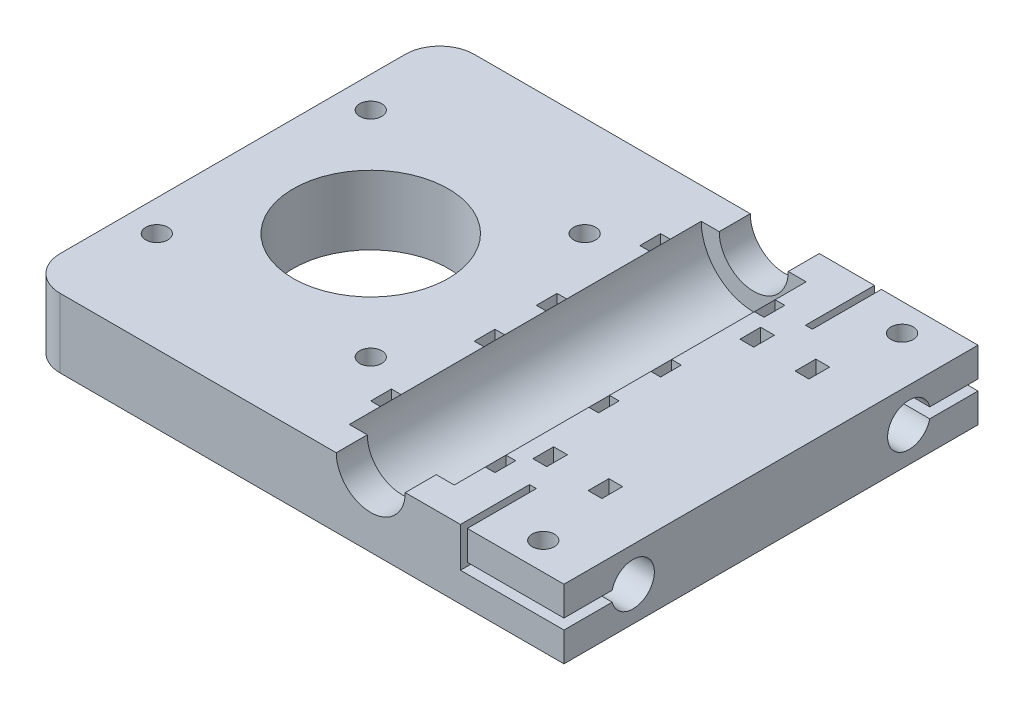
SolidWorks part; units mm, degrees
ref_plane "前基準面" through (0, 0, 0) normal (0, 0, 1) x (1, 0, 0)
ref_plane "上基準面" through (0, 0, 0) normal (0, 1, 0) x (1, 0, 0)
ref_plane "右基準面" through (0, 0, 0) normal (1, 0, 0) x (0, 0, -1)
sketch "草圖2" plane through (0, 0, 0) normal (0, 1, 0) x (1, 0, 0)
  line L1 (-20000, 30000) -> (20000, 30000)
  line L2 (-20000, 30000) -> (-20000, -30000)
  line L3 (-20000, -30000) -> (20000, -30000)
  line L4 (20000, 30000) -> (20000, -30000)
  line L5 (-20000, 30000) -> (20000, -30000) construction
  line L6 (-20000, -30000) -> (20000, 30000) construction
  point P0 (0, 0)
  dimension "D1" = 40000
  dimension "D2" = 60000
extrude "填料-伸長1" add sketch "草圖2" along normal blind 10000
sketch "草圖4" plane through (0, 0, 0) normal (0, 0, 1) x (1, 0, 0)
  line L0 (-20000, 10000) -> (20000, 10000) construction
  line L1 (-20000, 10000) -> (-20000, 0) construction
  circle A0 centre (-8000, 10000) radius 7600
  dimension "D1" = 15200
  dimension "D2" = 12000
extrude "除料-伸長2" cut sketch "草圖4" against normal mid plane 51000
sketch "草圖5" plane through (0, 0, 0) normal (0, 0, 1) x (1, 0, 0)
  circle A0 centre (-8000, 10000) radius 5000
  dimension "D1" = 10000
extrude "除料-伸長3" cut sketch "草圖5" against normal mid plane 80000
sketch "草圖6" plane through (0, 10000, 0) normal (0, 1, 0) x (1, 0, 0)
  line L0 (7000, 30000) -> (7000, -30000) construction
  line L1 (20000, 30000) -> (-3000, 30000) construction
  line L2 (-3000, -30000) -> (20000, -30000) construction
  line L3 (-13000, 25500) -> (-3000, 25500) construction
  line L4 (-20000, 0) -> (38738.6802, 0) construction
  line L5 (4000, 16500) -> (10000, 16500) construction
  line L6 (4000, 16500) -> (4000, 13500) construction
  line L7 (4000, 13500) -> (10000, 13500) construction
  line L8 (10000, 16500) -> (10000, 13500) construction
  line L9 (4000, 16500) -> (10000, 13500) construction
  line L10 (4000, 13500) -> (10000, 16500) construction
  line L11 (-20000, 30000) -> (-20000, -30000) construction
  line L12 (12000, -16500) -> (12000, -13500)
  line L13 (4000, 16500) -> (2000, 16500)
  line L14 (4000, 16500) -> (4000, 13500)
  line L15 (4000, 13500) -> (2000, 13500)
  line L16 (2000, 16500) -> (2000, 13500)
  line L17 (10000, 16500) -> (12000, 16500)
  line L18 (10000, 16500) -> (10000, 13500)
  line L19 (10000, 13500) -> (12000, 13500)
  line L20 (12000, 16500) -> (12000, 13500)
  line L21 (10000, -16500) -> (12000, -16500)
  line L22 (10000, -16500) -> (10000, -13500)
  line L23 (4000, -13500) -> (2000, -13500)
  line L24 (10000, -13500) -> (12000, -13500)
  line L25 (4000, -16500) -> (4000, -13500)
  line L26 (2000, -16500) -> (2000, -13500)
  line L27 (4000, -16500) -> (2000, -16500)
  point P8 (-8000, 25500)
  point P9 (7000, 15000)
  dimension "D1" = 15000
  dimension "D2" = 6000
  dimension "D3" = 3000
  dimension "D4" = 15000
  dimension "D5" = 2000
  dimension "D6" = 2000
extrude "除料-伸長4" cut sketch "草圖6" against normal blind 80000
sketch "草圖10" plane through (0, 10000, 0) normal (0, 1, 0) x (1, 0, 0)
  line L1 (-53500, -15500) -> (-53500, 15500) construction
  line L2 (-53500, -15500) -> (-22500, -15500) construction
  line L3 (-22500, -15500) -> (-22500, 15500) construction
  line L4 (-53500, 15500) -> (-22500, 15500) construction
  line L5 (-53500, -15500) -> (-22500, 15500) construction
  line L6 (-22500, -15500) -> (-53500, 15500) construction
  line L8 (-8000, 25500) -> (-8000, -13906.3177) construction
  line L9 (-13000, 25500) -> (-3000, 25500) construction
  point P0 (-38000, 0)
  dimension "D1" = 31000
  dimension "D2" = 31000
  dimension "D3" = 30000
sketch "草圖12" plane through (0, 10000, 0) normal (0, 1, 0) x (1, 0, 0)
  line L0 (-53500, -15500) -> (-22500, 15500) construction
  line L1 (-20000, 30000) -> (-58000, 30000)
  line L2 (-20000, 30000) -> (-20000, -30000)
  line L3 (-20000, -30000) -> (-58000, -30000)
  line L4 (-58000, 30000) -> (-58000, -30000)
  line L5 (-20000, -30000) -> (-13000, -30000) construction
  circle A0 centre (-53500, 15500) radius 1600
  circle A1 centre (-22500, 15500) radius 1600
  circle A2 centre (-53500, -15500) radius 1600
  circle A3 centre (-22500, -15500) radius 1600
  circle A4 centre (-38000, 0) radius 11250
  dimension "D2" = 3200
  dimension "D3" = 3200
  dimension "D4" = 3200
  dimension "D5" = 3200
  dimension "D6" = 22500
  dimension "D1" = 38000
extrude "填料-伸長2" add sketch "草圖12" against normal blind 10000
sketch "草圖13" plane through (20000, 0, 0) normal (1, 0, 0) x (0, 0, -1)
  line L0 (0, 11922.9918) -> (0, -4401.0139) construction
  circle A0 centre (-20000, 5000) radius 3100
  circle A1 centre (20000, 5000) radius 3100
  dimension "D1" = 6200
  dimension "D2" = 20000
extrude "除料-伸長6" cut sketch "草圖13" against normal blind 18000
sketch "草圖15" plane through (0, 10000, 0) normal (0, 1, 0) x (1, 0, 0)
  line L0 (-22500, -15500) -> (-53500, 15500) construction
  line L1 (-59000, -21000) -> (-17000, -21000) construction
  line L2 (-59000, -21000) -> (-59000, 21000) construction
  line L3 (-59000, 21000) -> (-17000, 21000) construction
  line L4 (-17000, -21000) -> (-17000, 21000) construction
  line L5 (-59000, -21000) -> (-17000, 21000) construction
  line L6 (-59000, 21000) -> (-17000, -21000) construction
  point P0 (-38000, 0)
  dimension "D1" = 42000
  dimension "D2" = 42000
sketch "草圖16" plane through (20000, 0, 0) normal (1, 0, 0) x (0, 0, -1)
  line L0 (0, 10000) -> (0, -6413.2276) construction
  line L1 (-20000, 5000) -> (-32080.4356, 5000) construction
  line L2 (31055.9576, 4250) -> (21024.478, 5750) construction
  line L3 (-31055.9576, 5750) -> (-21024.478, 5750)
  line L4 (-31055.9576, 5750) -> (-31055.9576, 4250)
  line L5 (-31055.9576, 4250) -> (-21024.478, 4250)
  line L6 (-21024.478, 5750) -> (-21024.478, 4250)
  line L7 (-31055.9576, 5750) -> (-21024.478, 4250) construction
  line L8 (-31055.9576, 4250) -> (-21024.478, 5750) construction
  line L9 (31055.9576, 5750) -> (21024.478, 4250) construction
  line L10 (20000, 5000) -> (32080.4356, 5000) construction
  line L11 (21024.478, 5750) -> (21024.478, 4250)
  line L12 (31055.9576, 4250) -> (21024.478, 4250)
  line L13 (31055.9576, 5750) -> (31055.9576, 4250)
  line L14 (31055.9576, 5750) -> (21024.478, 5750)
  point P2 (-26040.2178, 5000)
  point P18 (26040.2178, 5000)
  dimension "D1" = 10031.4796
  dimension "D2" = 1500
extrude "除料-伸長7" cut sketch "草圖16" against normal blind 15000
sketch "草圖17" plane through (0, 10000, 0) normal (0, 1, 0) x (1, 0, 0)
  line L0 (20320.3387, 0) -> (-9687.0538, 0) construction
  line L1 (5000, 30000) -> (6000, 30000)
  line L2 (5000, 30000) -> (5000, 20000)
  line L3 (5000, 20000) -> (6000, 20000)
  line L4 (6000, 30000) -> (6000, 20000)
  line L5 (6000, -30000) -> (6000, -20000)
  line L6 (5000, -20000) -> (6000, -20000)
  line L7 (5000, -30000) -> (5000, -20000)
  line L8 (5000, -30000) -> (6000, -30000)
  dimension "D1" = 1000
  dimension "D2" = 10000
extrude "除料-伸長8" cut sketch "草圖17" against normal up to surface (5750 mm away) up to face at (12500, 4250, -26503.9531)
sketch "草圖18" plane through (0, 10000, 0) normal (0, 1, 0) x (1, 0, 0)
  line L0 (0, 0) -> (36287.083, 0) construction
  line L1 (20000, 30000) -> (6000, 30000) construction
  circle A0 centre (13000, 26000) radius 1600
  circle A1 centre (13000, -26000) radius 1600
  dimension "D1" = 3200
  dimension "D2" = 4000
extrude "除料-伸長9" cut sketch "草圖18" against normal blind 15000
sketch "草圖19" plane through (0, 10000, 0) normal (0, 1, 0) x (1, 0, 0)
  line L0 (-15600, 0) -> (22136.2106, 0) construction
  line L1 (-15600, 25500) -> (-15600, -25500) construction
  line L2 (-15600, 12000) -> (5685.0909, 12000) construction
  line L3 (-15600, -12000) -> (2799.4169, -12000) construction
  line L4 (-17000, -21000) -> (-17000, 21000) construction
  line L5 (-15600, 21000) -> (-17000, 21000)
  line L6 (-15600, 21000) -> (-15600, 18000)
  line L7 (-15600, 18000) -> (-17000, 18000)
  line L8 (-17000, 21000) -> (-17000, 18000)
  line L9 (-59000, 21000) -> (-17000, 21000) construction
  line L10 (-15600, 3000) -> (-15600, 6000)
  line L11 (-15600, 6000) -> (-17000, 6000)
  line L12 (-17000, 3000) -> (-17000, 6000)
  line L13 (-15600, 3000) -> (-17000, 3000)
  line L14 (-15600, -3000) -> (-17000, -3000)
  line L15 (-17000, -3000) -> (-17000, -6000)
  line L16 (-15600, -6000) -> (-17000, -6000)
  line L17 (-15600, -3000) -> (-15600, -6000)
  line L18 (-17000, -21000) -> (-17000, -18000)
  line L19 (-15600, -18000) -> (-17000, -18000)
  line L20 (-15600, -21000) -> (-15600, -18000)
  line L21 (-15600, -21000) -> (-17000, -21000)
  line L22 (-8000, 25500) -> (-8000, -25500) construction
  line L23 (-13000, 25500) -> (-3000, 25500) construction
  line L24 (-400, -25500) -> (-15600, -25500) construction
  line L25 (-400, -21000) -> (1000, -21000)
  line L26 (-400, -21000) -> (-400, -18000)
  line L27 (-400, -18000) -> (1000, -18000)
  line L28 (1000, -21000) -> (1000, -18000)
  line L29 (-400, -3000) -> (-400, -6000)
  line L30 (-400, -6000) -> (1000, -6000)
  line L31 (1000, -3000) -> (1000, -6000)
  line L32 (-400, -3000) -> (1000, -3000)
  line L33 (-400, 3000) -> (1000, 3000)
  line L34 (1000, 3000) -> (1000, 6000)
  line L35 (-400, 6000) -> (1000, 6000)
  line L36 (-400, 3000) -> (-400, 6000)
  line L37 (1000, 21000) -> (1000, 18000)
  line L38 (-400, 18000) -> (1000, 18000)
  line L39 (-400, 21000) -> (-400, 18000)
  line L40 (-400, 21000) -> (1000, 21000)
  point P17 (-15600, 19500)
  point P18 (-15600, 4500)
  point P27 (-15600, -4500)
  point P54 (-400, -4500)
  point P55 (-400, 4500)
  dimension "D1" = 12000
  dimension "D2" = 12000
  dimension "D3" = 3000
extrude "除料-伸長10" cut sketch "草圖19" against normal blind 15000
fillet "圓角1" radius 5000 2 edges at (-58000, 5000, -30000) (-58000, 5000, 30000)
sketch "草圖20" plane through (0, 0, 0) normal (0, -1, 0) x (1, 0, 0)
  line L1 (4000, 16500) -> (10000, 16500)
  line L2 (4000, 16500) -> (4000, 13500)
  line L3 (4000, 13500) -> (10000, 13500)
  line L4 (10000, 16500) -> (10000, 13500)
  line L5 (4000, -13500) -> (10000, -13500)
  line L6 (4000, -13500) -> (4000, -16500)
  line L7 (4000, -16500) -> (10000, -16500)
  line L8 (10000, -13500) -> (10000, -16500)
extrude "除料-伸長11" cut sketch "草圖20" against normal blind 2000
fillet "圓角2" radius 1000 4 edges at (4000, 2000, -15000) (10000, 2000, -15000) (10000, 2000, 15000) (4000, 2000, 15000)
